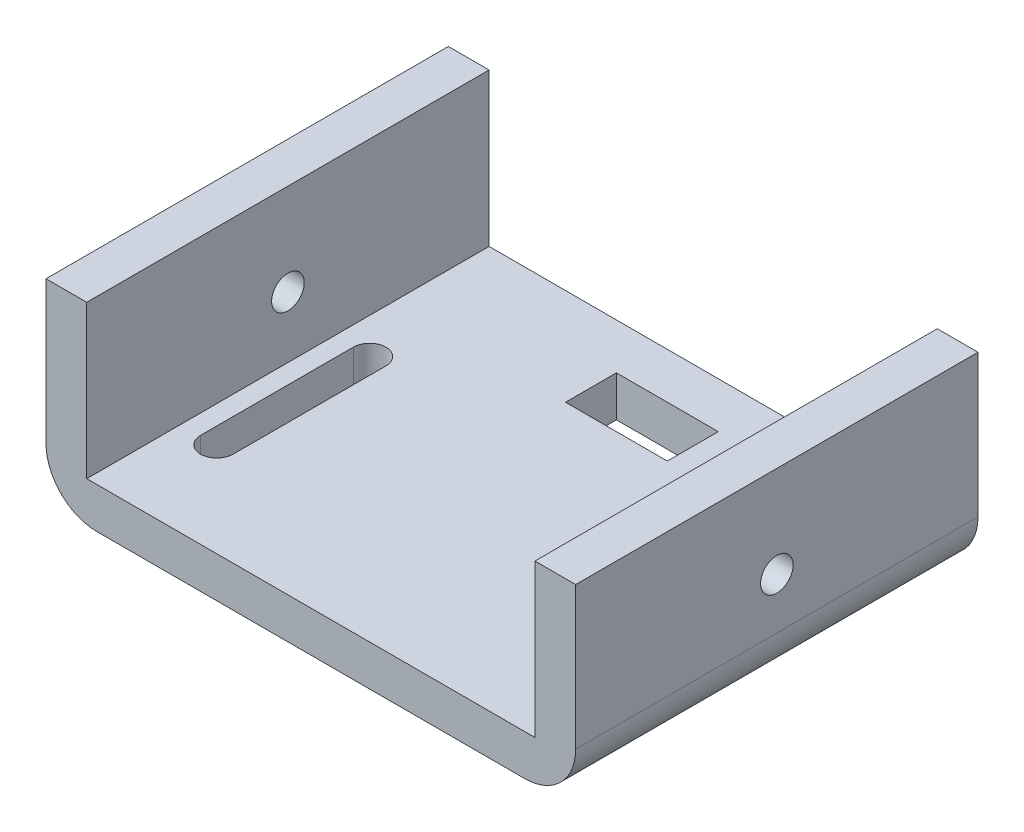
SolidWorks part; units mm, degrees
ref_plane "Plan de face" through (0, 0, 0) normal (0, 0, 1) x (1, 0, 0)
ref_plane "Plan de dessus" through (0, 0, 0) normal (0, 1, 0) x (1, 0, 0)
ref_plane "Plan de droite" through (0, 0, 0) normal (1, 0, 0) x (0, 0, -1)
sketch "Esquisse1" plane through (0, 0, 0) normal (0, 0, 1) x (1, 0, 0)
  line L0 (-22, 0) -> (22, 0)
  line L5 (22, 0) -> (22, 15)
  line L6 (0, 21.1762) -> (0, 6.9257) construction
  line L7 (-22, 0) -> (-22, 15)
  line L8 (-22, 15) -> (-26, 15)
  line L9 (-26, 15) -> (-26, -4)
  line L10 (-26, -4) -> (26, -4)
  line L11 (26, -4) -> (26, 15)
  line L12 (26, 15) -> (22, 15)
  point P8 (0, 0)
  dimension "D1" = 22
  dimension "D2" = 15
  dimension "D3" = 4
  dimension "D4" = 4
  dimension "D5" = 4
  dimension "D6" = 4
extrude "Boss.-Extru.1" add sketch "Esquisse1" along normal blind 39.5
ref_plane "Plan1" through (179.5, -192, -20) normal (-1, 0, 0) x (0, 0, 1)
sketch "Esquisse3" plane through (0, -4, 0) normal (0, -1, 0) x (1, 0, 0)
  line L1 (5, 4.5) -> (-5, 4.5)
  line L2 (5, 4.5) -> (5, 9.5)
  line L3 (5, 9.5) -> (-5, 9.5)
  line L4 (-5, 4.5) -> (-5, 9.5)
  line L5 (5, 4.5) -> (-5, 9.5) construction
  line L6 (5, 9.5) -> (-5, 4.5) construction
  line L7 (-26, 39.5) -> (26, 39.5) construction
  line L8 (-26, 0) -> (26, 0) construction
  point P0 (0, 0)
  point P4 (0, 0)
  point P6 (0, 7)
  dimension "D1" = 10
  dimension "D2" = 5
  dimension "D4" = 30
extrude "Enlèv. mat.-Extru.1" cut sketch "Esquisse3" against normal through all
sketch "Sketch1" plane through (-22, 0, 0) normal (1, 0, 0) x (0, 0, -1)
  circle A0 centre (-19.75, 6) radius 1.6
extrude "Cut-Extrude1" cut sketch "Sketch1" against normal through all and the other way through all
sketch "Sketch2" plane through (0, -4, 0) normal (0, -1, 0) x (1, 0, 0)
  line L0 (-18.5, 30.2269) -> (-18.5, 15.2269) construction
  line L1 (-16.9, 30.2269) -> (-16.9, 15.2269)
  line L2 (-20.1, 30.2269) -> (-20.1, 15.2269)
  line L3 (18.5, 30.2269) -> (18.5, 15.2269) construction
  line L4 (20.1, 30.2269) -> (20.1, 15.2269)
  line L5 (16.9, 30.2269) -> (16.9, 15.2269)
  arc A1 (-16.9, 30.2269) -> (-20.1, 30.2269) centre (-18.5, 30.2269) ccw
  arc A2 (-20.1, 15.2269) -> (-16.9, 15.2269) centre (-18.5, 15.2269) ccw
  arc A3 (20.1, 30.2269) -> (16.9, 30.2269) centre (18.5, 30.2269) ccw
  arc A4 (16.9, 15.2269) -> (20.1, 15.2269) centre (18.5, 15.2269) ccw
  point P3 (-18.5, 22.7269)
  point P12 (18.5, 22.7269)
  dimension "D1" = 1.6
  dimension "D2" = 15
extrude "Cut-Extrude2" cut sketch "Sketch2" against normal through all
fillet "Fillet1" radius 5 2 edges at (26, -4, 19.75) (-26, -4, 19.75)
